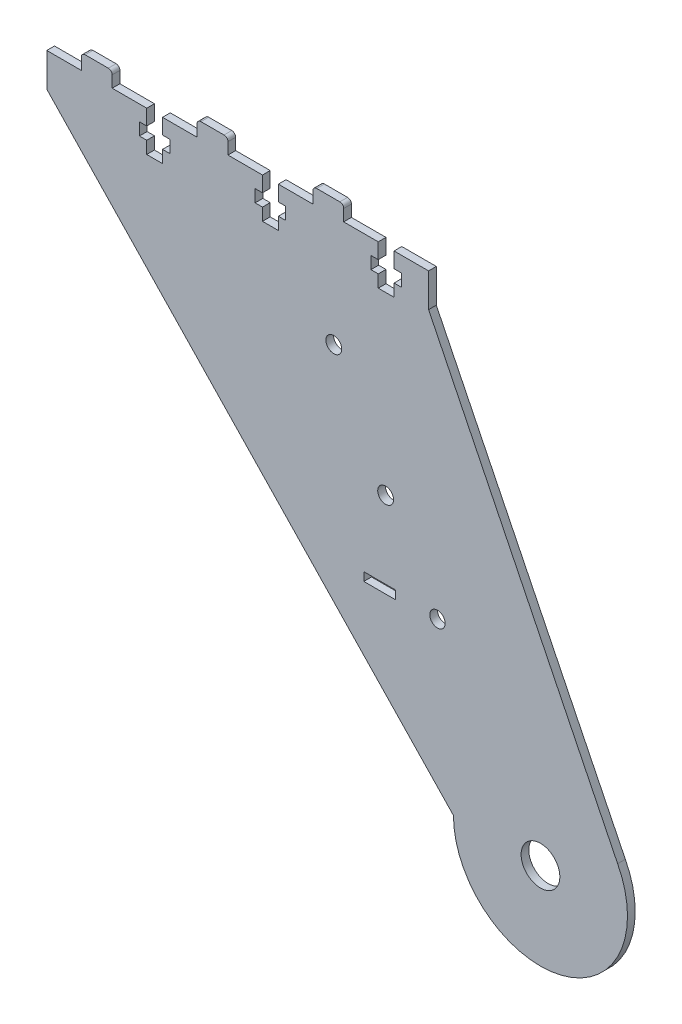
SolidWorks part; units mm, degrees
ref_plane "前视基准面" through (0, 0, 0) normal (0, 0, 1) x (1, 0, 0)
ref_plane "上视基准面" through (0, 0, 0) normal (0, 1, 0) x (1, 0, 0)
ref_plane "右视基准面" through (0, 0, 0) normal (1, 0, 0) x (0, 0, -1)
sketch "草图1" plane through (0, 0, 0) normal (0, 0, 1) x (1, 0, 0)
  line L0 (-19.7627, 31.422) -> (7.0984, -10.75) construction
  line L2 (-36.2, 68.25) -> (-36.2, 58.15) construction
  line L15 (-38.25, 66.25) -> (-38.25, 62.25)
  line L16 (-38.25, 62.25) -> (-40.15, 62.25)
  line L17 (-40.15, 62.25) -> (-40.15, 59.05)
  line L18 (-40.15, 59.05) -> (-38.25, 59.05)
  line L19 (-38.25, 59.05) -> (-38.25, 55.85)
  line L20 (-38.25, 55.85) -> (-34.15, 55.85)
  line L21 (-38.25, 66.25) -> (-47.2, 66.25)
  line L22 (-51.2, 66.25) -> (-51.2, 70.25) construction
  line L23 (-47.2, 66.25) -> (-55.2, 66.25) construction
  line L24 (-47.2, 66.25) -> (-47.2, 70.25)
  line L25 (-47.2, 70.25) -> (-55.2, 70.25)
  line L26 (-55.2, 66.25) -> (-55.2, 70.25)
  line L27 (-25.2, 66.25) -> (-17.2, 66.25) construction
  line L28 (-21.2, 66.25) -> (-21.2, 70.25) construction
  line L29 (-17.2, 66.25) -> (-17.2, 70.25)
  line L30 (-25.2, 70.25) -> (-17.2, 70.25)
  line L31 (-25.2, 66.25) -> (-25.2, 70.25)
  line L32 (-34.15, 66.25) -> (-25.2, 66.25)
  line L33 (-34.15, 59.05) -> (-34.15, 55.85)
  line L34 (-32.25, 59.05) -> (-34.15, 59.05)
  line L35 (-32.25, 62.25) -> (-32.25, 59.05)
  line L36 (-34.15, 62.25) -> (-32.25, 62.25)
  line L37 (-34.15, 66.25) -> (-34.15, 62.25)
  line L38 (-94.15, 66.25) -> (-94.15, 57.55)
  line L40 (-68.25, 66.25) -> (-68.25, 62.25)
  line L41 (-68.25, 62.25) -> (-70.15, 62.25)
  line L42 (-70.15, 62.25) -> (-70.15, 59.05)
  line L43 (-70.15, 59.05) -> (-68.25, 59.05)
  line L44 (-68.25, 59.05) -> (-68.25, 55.85)
  line L45 (-68.25, 66.25) -> (-77.2, 66.25)
  line L46 (-6.2, 68.25) -> (-6.2, 58.15) construction
  line L49 (-64.15, 55.85) -> (-68.25, 55.85)
  line L50 (-64.15, 59.05) -> (-64.15, 55.85)
  line L51 (-62.25, 59.05) -> (-64.15, 59.05)
  line L52 (-62.25, 62.25) -> (-62.25, 59.05)
  line L53 (-64.15, 62.25) -> (-62.25, 62.25)
  line L54 (-64.15, 66.25) -> (-64.15, 62.25)
  line L55 (-55.2, 66.25) -> (-64.15, 66.25)
  line L58 (-8.25, 66.25) -> (-17.2, 66.25)
  line L59 (-94.15, 66.25) -> (-85.2, 66.25)
  line L60 (-85.2, 66.25) -> (-85.2, 70.25)
  line L61 (-77.2, 70.25) -> (-85.2, 70.25)
  line L62 (-77.2, 66.25) -> (-77.2, 70.25)
  line L63 (4.8, 66.25) -> (4.8, 57.55)
  line L65 (7.0984, -10.75) -> (-7.9016, -10.75) construction
  line L66 (-8.25, 66.25) -> (-8.25, 62.25)
  line L67 (-8.25, 62.25) -> (-10.15, 62.25)
  line L68 (-10.15, 62.25) -> (-10.15, 59.05)
  line L69 (-10.15, 59.05) -> (-8.25, 59.05)
  line L70 (-8.25, 59.05) -> (-8.25, 55.85)
  line L74 (-4.15, 66.25) -> (4.8, 66.25)
  line L75 (-4.15, 55.85) -> (-8.25, 55.85)
  line L76 (-4.15, 59.05) -> (-4.15, 55.85)
  line L77 (-2.25, 59.05) -> (-4.15, 59.05)
  line L78 (-2.25, 62.25) -> (-2.25, 59.05)
  line L79 (-4.15, 62.25) -> (-2.25, 62.25)
  line L80 (-4.15, 66.25) -> (-4.15, 62.25)
  line L87 (-12.0016, -11.85) -> (-3.8016, -11.85)
  line L88 (-12.0016, -11.85) -> (-12.0016, -9.65)
  line L89 (-12.0016, -9.65) -> (-3.8016, -9.65)
  line L90 (-3.8016, -11.85) -> (-3.8016, -9.65)
  line L91 (-12.0016, -11.85) -> (-3.8016, -9.65) construction
  line L92 (-12.0016, -9.65) -> (-3.8016, -11.85) construction
  line L100 (53.7933, -42.3195) -> (4.8, 57.55)
  line L113 (-94.15, 57.55) -> (11.24, -52.75)
  line L135 (-19.7627, 31.422) -> (-19.7627, 37.422) construction
  circle A0 centre (-36.2, 68.25) radius 2.05 construction
  circle A1 centre (-19.7627, 31.422) radius 2 construction
  circle A2 centre (7.0984, -10.75) radius 2
  circle A3 centre (33.795, -52.75) radius 22.555 construction
  circle A7 centre (33.795, -52.75) radius 5.02
  circle A8 centre (-6.3322, 10.336) radius 2.05
  arc A14 (11.24, -52.75) -> (53.7933, -42.3195) centre (33.795, -52.75) ccw
  circle A20 centre (-19.7627, 37.422) radius 2.05
  point P39 (-36.2, 55.85)
  point P61 (-66.2, 55.85)
  point P91 (-6.2, 55.85)
  dimension "D17" = 10.04
  dimension "D20" = 4
  dimension "D12" = 4.1
  dimension "D5" = 4
  dimension "D6" = 2
  dimension "D7" = 3.2
  dimension "D8" = 3.2
  dimension "D9" = 15
  dimension "D10" = 8
  dimension "D11" = 4
  dimension "D13" = 8.2
  dimension "D14" = 2.2
  dimension "D15" = 10.1
  dimension "D16" = 15
extrude "凸台-拉伸1" add sketch "草图1" along normal blind 2
sketch "草图2" plane through (0, 66.25, 0) normal (0, 1, 0) x (1, 0, 0)
  line L0 (-8.25, -1) -> (-4.15, -1)
  line L1 (-8.25, -2) -> (-8.25, 0) construction
  line L2 (-4.15, -2) -> (-4.15, 0) construction
  circle A0 centre (-6.2, -1) radius 2.05
fillet "圆角1" radius 1 6 edges at (-17.2, 70.25, 1) (-25.2, 70.25, 1) (-47.2, 70.25, 1) (-55.2, 70.25, 1) (-77.2, 70.25, 1) (-85.2, 70.25, 1)
